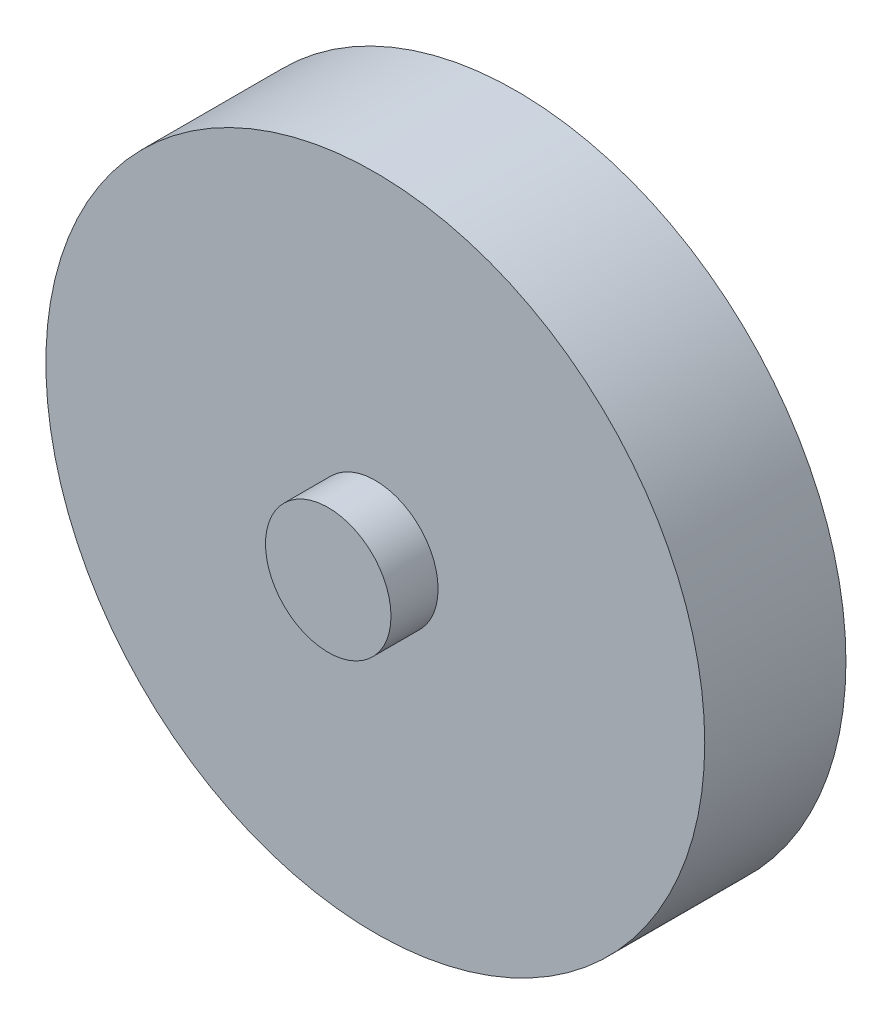
SolidWorks part; units mm, degrees
ref_plane "前视基准面" through (0, 0, 0) normal (0, 0, 1) x (1, 0, 0)
ref_plane "上视基准面" through (0, 0, 0) normal (0, 1, 0) x (1, 0, 0)
ref_plane "右视基准面" through (0, 0, 0) normal (1, 0, 0) x (0, 0, -1)
other "Configuration Table"
sketch "草图1" plane through (0, 0, 0) normal (0, 0, 1) x (1, 0, 0)
  circle A0 centre (0, 0) radius 8
extrude "凸台-拉伸1" add sketch "草图1" along normal blind 24
sketch "草图2" plane through (0, 0, 0) normal (0, 0, 1) x (1, 0, 0)
  circle A0 centre (0, 0) radius 42
extrude "凸台-拉伸2" add sketch "草图2" along normal blind 18
sketch "草图3" plane through (0, 0, 18) normal (0, 0, 1) x (1, 0, 0)
  line L0 (20, 32) -> (20, 24)
